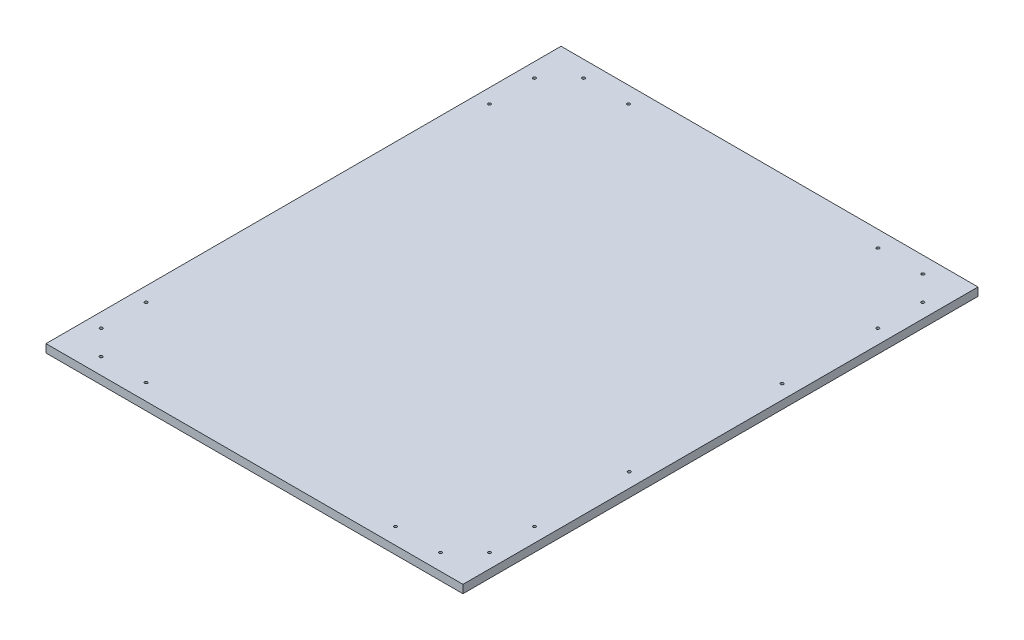
SolidWorks part; units mm, degrees
ref_plane "Front Plane" through (0, 0, 0) normal (0, 0, 1) x (1, 0, 0)
ref_plane "Top Plane" through (0, 0, 0) normal (0, 1, 0) x (1, 0, 0)
ref_plane "Right Plane" through (0, 0, 0) normal (1, 0, 0) x (0, 0, -1)
sketch "Sketch1" plane through (0, 0, 0) normal (0, 1, 0) x (1, 0, 0)
  line L0 (0, 0) -> (0, 630)
  line L1 (0, 0) -> (510, 0)
  line L2 (510, 0) -> (510, 630)
  line L3 (510, 630) -> (0, 630)
  dimension "D1" = 630
  dimension "D2" = 510
extrude "Boss-Extrude1" add sketch "Sketch1" along normal blind 10
sketch "Sketch2" plane through (0, 10, 0) normal (0, 1, 0) x (1, 0, 0)
  line L1 (0, 0) -> (510, 0) construction
  line L2 (510, 0) -> (510, 630) construction
  line L3 (510, 630) -> (0, 630) construction
  circle A0 centre (492.5, 50) radius 1.8
  circle A4 centre (492.5, 105) radius 1.8
  circle A5 centre (492.5, 580) radius 1.8
  circle A6 centre (492.5, 525) radius 1.8
  circle A7 centre (492.5, 407.8288) radius 1.8
  circle A8 centre (492.5, 221) radius 1.8
  dimension "D5" = 3.6
  dimension "D7" = 3.6
  dimension "D8" = 3.6
  dimension "D9" = 3.6
  dimension "D13" = 3.6
  dimension "D14" = 3.6
  dimension "D1" = 55
  dimension "D2" = 50
  dimension "D3" = 55
  dimension "D4" = 50
  dimension "D6" = 17.5
  dimension "D10" = 17.5
  dimension "D11" = 17.5
  dimension "D12" = 17.5
  dimension "D15" = 17.5
  dimension "D16" = 17.5
  dimension "D17" = 116
extrude "Cut-Extrude1" cut sketch "Sketch2" against normal blind 10
sketch "Sketch3" plane through (0, 10, 0) normal (0, 1, 0) x (1, 0, 0)
  line L0 (0, 630) -> (0, 0) construction
  line L1 (510, 630) -> (0, 630) construction
  line L2 (0, 0) -> (510, 0) construction
  circle A0 centre (17.5, 50) radius 1.8
  circle A1 centre (17.5, 105) radius 1.8
  circle A2 centre (17.5, 525) radius 1.8
  circle A3 centre (17.5, 580) radius 1.8
  dimension "D9" = 3.6
  dimension "D10" = 3.6
  dimension "D11" = 3.6
  dimension "D12" = 3.6
  dimension "D1" = 17.5
  dimension "D2" = 17.5
  dimension "D3" = 50
  dimension "D4" = 55
  dimension "D5" = 17.5
  dimension "D6" = 17.5
  dimension "D7" = 55
  dimension "D8" = 50
extrude "Cut-Extrude2" cut sketch "Sketch3" against normal blind 10
sketch "Sketch4" plane through (0, 10, 0) normal (0, 1, 0) x (1, 0, 0)
  line L0 (510, 630) -> (0, 630) construction
  line L1 (0, 630) -> (0, 0) construction
  line L2 (510, 0) -> (510, 630) construction
  line L3 (0, 0) -> (510, 0) construction
  circle A0 centre (47.5, 610) radius 1.8
  circle A1 centre (102.5, 610) radius 1.8
  circle A2 centre (407.5, 610) radius 1.8
  circle A3 centre (462.5, 610) radius 1.8
  circle A4 centre (462.5, 20) radius 1.8
  circle A5 centre (407.5, 20) radius 1.8
  circle A6 centre (102.5, 20) radius 1.8
  circle A7 centre (47.5, 20) radius 1.8
  dimension "D9" = 3.6
  dimension "D10" = 3.6
  dimension "D11" = 3.6
  dimension "D12" = 3.6
  dimension "D19" = 3.6
  dimension "D22" = 3.6
  dimension "D23" = 3.6
  dimension "D24" = 3.6
  dimension "D1" = 20
  dimension "D2" = 47.5
  dimension "D3" = 55
  dimension "D4" = 20
  dimension "D5" = 20
  dimension "D6" = 20
  dimension "D7" = 47.5
  dimension "D8" = 55
  dimension "D13" = 47.5
  dimension "D14" = 20
  dimension "D15" = 20
  dimension "D16" = 55
  dimension "D17" = 55
  dimension "D18" = 47.5
  dimension "D20" = 20
  dimension "D21" = 20
extrude "Cut-Extrude3" cut sketch "Sketch4" against normal blind 12.1
